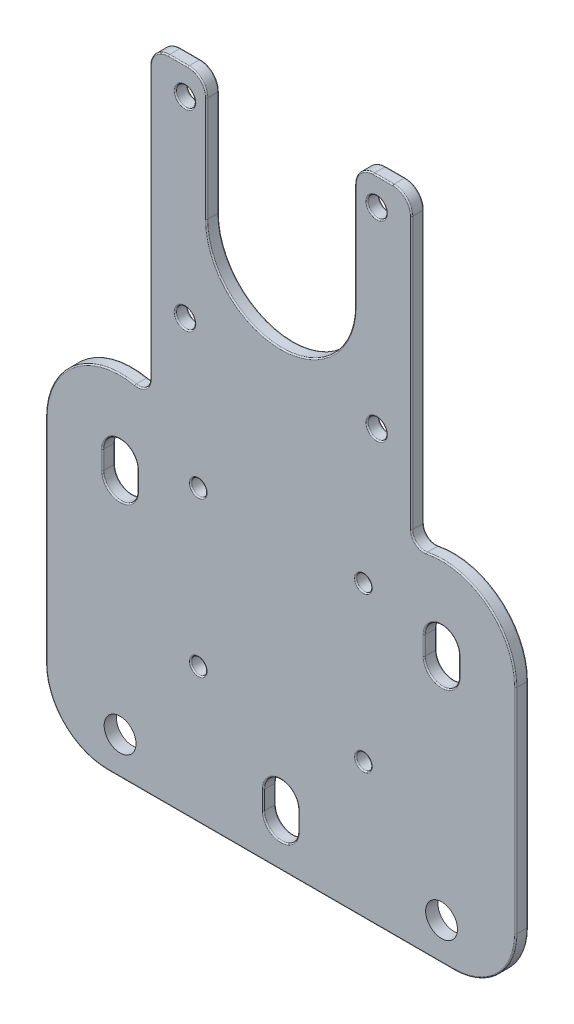
SolidWorks part; units mm, degrees
ref_plane "前视基准面" through (0, 0, 0) normal (0, 0, 1) x (1, 0, 0)
ref_plane "上视基准面" through (0, 0, 0) normal (0, 1, 0) x (1, 0, 0)
ref_plane "右视基准面" through (0, 0, 0) normal (1, 0, 0) x (0, 0, -1)
sketch "草图1" plane through (0, 0, 0) normal (0, 0, 1) x (1, 0, 0)
  line L0 (-21.15, 56.6196) -> (-21.15, 12.7264)
  line L1 (-26, -0.9804) -> (-26, -3.9804) construction
  line L2 (-15, 59.6196) -> (-18.15, 59.6196)
  line L3 (18.15, 59.6196) -> (15, 59.6196)
  line L4 (38, -0.9804) -> (38, -45.4804)
  line L5 (21.15, 56.6196) -> (21.15, 12.7264)
  line L6 (-26, -2.4804) -> (1.7366, -2.4804) construction
  line L7 (-12, 39.6196) -> (-12, 56.6196)
  line L8 (12, 39.6196) -> (12, 56.6196)
  line L9 (-28.8, -0.9804) -> (-28.8, -3.9804)
  line L10 (-23.2, -0.9804) -> (-23.2, -3.9804)
  line L11 (-28.8, -0.9804) -> (-28.8, -3.9804)
  line L12 (-23.2, -0.9804) -> (-23.2, -3.9804)
  line L13 (0, -2.4804) -> (0, -36.8304) construction
  line L14 (-38, -3.9804) -> (-26, -3.9804) construction
  line L15 (0, 39.6196) -> (0, -65.8157) construction
  line L16 (38, -45.4804) -> (-38, -45.4804)
  line L17 (-38, -0.9804) -> (-38, -45.4804)
  line L18 (-28.8, -0.9804) -> (-28.8, -3.9804)
  line L19 (-23.2, -0.9804) -> (-23.2, -3.9804)
  line L20 (-28.8, -0.9804) -> (-28.8, -3.9804)
  line L21 (-23.2, -0.9804) -> (-23.2, -3.9804)
  line L22 (-28.8, -0.9804) -> (-28.8, -3.9804)
  line L23 (-23.2, -0.9804) -> (-23.2, -3.9804)
  line L24 (-28.8, -0.9804) -> (-28.8, -3.9804)
  line L25 (-23.2, -0.9804) -> (-23.2, -3.9804)
  line L26 (-28.8, -0.9804) -> (-28.8, -3.9804)
  line L27 (-23.2, -0.9804) -> (-23.2, -3.9804)
  line L28 (-28.8, -0.9804) -> (-28.8, -3.9804)
  line L29 (-23.2, -0.9804) -> (-23.2, -3.9804)
  line L30 (28.8, -0.9804) -> (28.8, -3.9804)
  line L31 (23.2, -0.9804) -> (23.2, -3.9804)
  line L32 (2.8, -35.6304) -> (2.8, -38.6304)
  line L33 (2.8, -35.3304) -> (2.8, -38.3304)
  line L34 (0, -35.3304) -> (0, -38.3304) construction
  line L35 (2.8, -35.3304) -> (2.8, -38.3304)
  line L36 (2.8, -35.3304) -> (2.8, -38.3304)
  line L37 (2.8, -35.3304) -> (2.8, -38.3304)
  line L38 (-2.8, -35.6304) -> (-2.8, -38.6304)
  line L39 (-2.8, -35.3304) -> (-2.8, -38.3304)
  line L40 (-2.8, -35.3304) -> (-2.8, -38.3304)
  line L41 (-2.8, -35.3304) -> (-2.8, -38.3304)
  line L42 (2.8, -35.3304) -> (2.8, -38.3304)
  line L43 (-2.8, -35.3304) -> (-2.8, -38.3304)
  line L44 (2.8, -35.3304) -> (2.8, -38.3304)
  line L45 (2.8, -35.3304) -> (2.8, -38.3304)
  line L46 (-2.8, -35.3304) -> (-2.8, -38.3304)
  line L47 (-2.8, -35.3304) -> (-2.8, -38.3304)
  line L48 (-2.8, -35.3304) -> (-2.8, -38.3304)
  line L49 (0, -2.4804) -> (0, -37.1304) construction
  circle A2 centre (-15.5, 55.1196) radius 1.55
  circle A3 centre (15.5, 24.1196) radius 1.55
  circle A4 centre (-15.5, 24.1196) radius 1.55
  circle A5 centre (15.5, 55.1196) radius 1.55
  arc A6 (15, 59.6196) -> (12, 56.6196) centre (15, 56.6196) ccw
  arc A7 (-23.5571, 10.7683) -> (-21.15, 12.7264) centre (-23.15, 12.7264) ccw
  arc A8 (-23.5571, 10.7683) -> (-38, -0.9804) centre (-26, -0.9804) ccw
  arc A9 (23.5571, 10.7683) -> (21.15, 12.7264) centre (23.15, 12.7264) cw
  arc A10 (-18.15, 59.6196) -> (-21.15, 56.6196) centre (-18.15, 56.6196) ccw
  arc A11 (-12, 39.6196) -> (12, 39.6196) centre (0, 39.6196) ccw
  arc A12 (21.15, 56.6196) -> (18.15, 59.6196) centre (18.15, 56.6196) ccw
  arc A13 (23.5571, 10.7683) -> (38, -0.9804) centre (26, -0.9804) cw
  arc A14 (23.2, -0.9804) -> (28.8, -0.9804) centre (26, -0.9804) cw
  arc A15 (28.8, -3.9804) -> (23.2, -3.9804) centre (26, -3.9804) cw
  arc A16 (-12, 56.6196) -> (-15, 59.6196) centre (-15, 56.6196) ccw
  arc A17 (-23.2, -0.9804) -> (-28.8, -0.9804) centre (-26, -0.9804) ccw
  arc A18 (-28.8, -3.9804) -> (-23.2, -3.9804) centre (-26, -3.9804) ccw
  arc A19 (-2.8, -38.6304) -> (2.8, -38.6304) centre (0, -38.6304) ccw
  arc A20 (2.8, -35.6304) -> (-2.8, -35.6304) centre (0, -35.6304) ccw
  dimension "D3" = 12
  dimension "D4" = 2.8
  dimension "D6" = 35.5
  dimension "D1" = 2
  dimension "D9" = 56.1
  dimension "D11" = 2.8
  dimension "D12" = 4.5
  dimension "D2" = 34.65
  dimension "D5" = 31
  dimension "D7" = 5.65
  dimension "D8" = 5.65
  dimension "D10" = 26
extrude "凸台-拉伸2" add sketch "草图1" along normal blind 2 contours L7 A16 L2 A10 L0 A7 A8 L17 L16 L4 A13 A9 L5 A12 L3 A6 L8 A11 A20 L32 A19 L38 A18 L9 A17 L10 L30 A15 L31 A14 A2 A3 A4 A5
sketch "草图2" plane through (0, 0, 2) normal (0, 0, 1) x (1, 0, 0)
  line L0 (0, 27.6196) -> (0, -50.162) construction
  arc A0 (-12, 39.6196) -> (12, 39.6196) centre (0, 39.6196) ccw construction
sketch "草图3" plane through (0, 0, 2) normal (0, 0, 1) x (1, 0, 0)
  line L0 (38, -45.4804) -> (-38, -45.4804) construction
  line L1 (0, -41.4304) -> (0, 15.6863) construction
  line L2 (38, -0.9804) -> (38, -45.4804) construction
  circle A0 centre (13.35, 1.3996) radius 1.25
  circle A1 centre (13.35, -23.6004) radius 1.25
  arc A3 (-2.8, -38.6304) -> (2.8, -38.6304) centre (0, -38.6304) ccw construction
  circle A5 centre (-13.35, -23.6004) radius 1.25
  circle A7 centre (-13.35, 1.3996) radius 1.25
  dimension "D1" = 24.65
  dimension "D2" = 21.88
  dimension "D3" = 25
  dimension "D4" = 24.65
extrude "切除-拉伸1" cut sketch "草图3" against normal through all
fillet "圆角1" radius 10 2 edges at (38, -45.4804, 1) (-38, -45.4804, 1)
fillet "圆角2" radius 0.2 80 edges at (-35.0711, -42.5515, 2) (-38, -18.2304, 2) (-33.5725, 8.3285, 2) (-21.8879, 11.1749, 2) (-21.15, 34.673, 2) (-20.2713, 58.7409, 2) (-16.575, 59.6196, 2) (-12.8787, 58.7409, 2) (-12, 48.1196, 2) (0, 27.6196, 2) (12, 48.1196, 2) (12.8787, 58.7409, 2) (16.575, 59.6196, 2) (20.2713, 58.7409, 2) (21.15, 34.673, 2) (21.8879, 11.1749, 2) (33.5725, 8.3285, 2) (38, -18.2304, 2) (35.0711, -42.5515, 2) (0, -45.4804, 2) (17.05, 55.1196, 2) (-13.95, 24.1196, 2) (17.05, 24.1196, 2) (-13.95, 55.1196, 2) (26, 1.8196, 2) (23.2, -2.4804, 2) (26, -6.7804, 2) (28.8, -2.4804, 2) (-23.2, -2.4804, 2) (-26, 1.8196, 2) (-28.8, -2.4804, 2) (-26, -6.7804, 2) (-2.8, -37.1304, 2) (0, -41.4304, 2) (2.8, -37.1304, 2) (0, -32.8304, 2) (14.6, 1.3996, 2) (14.6, -23.6004, 2) (-14.6, -23.6004, 2) (-14.6, 1.3996, 2) (33.5725, 8.3285, 0) (21.8879, 11.1749, 0) (21.15, 34.673, 0) (20.2713, 58.7409, 0) (16.575, 59.6196, 0) (12.8787, 58.7409, 0) (12, 48.1196, 0) (0, 27.6196, 0) (-12, 48.1196, 0) (-12.8787, 58.7409, 0) (-16.575, 59.6196, 0) (-20.2713, 58.7409, 0) (-21.15, 34.673, 0) (-21.8879, 11.1749, 0) (-33.5725, 8.3285, 0) (-38, -18.2304, 0) (-35.0711, -42.5515, 0) (0, -45.4804, 0) (35.0711, -42.5515, 0) (38, -18.2304, 0) (17.05, 55.1196, 0) (-13.95, 24.1196, 0) (17.05, 24.1196, 0) (-13.95, 55.1196, 0) (26, -6.7804, 0) (23.2, -2.4804, 0) (26, 1.8196, 0) (28.8, -2.4804, 0) (-28.8, -2.4804, 0) (-26, 1.8196, 0) (-23.2, -2.4804, 0) (-26, -6.7804, 0) (2.8, -37.1304, 0) (0, -41.4304, 0) (-2.8, -37.1304, 0) (0, -32.8304, 0) (14.6, 1.3996, 0) (14.6, -23.6004, 0) (-14.6, -23.6004, 0) (-14.6, 1.3996, 0)
sketch "草图4" plane through (0, 0, 2) normal (0, 0, 1) x (1, 0, 0)
  line L0 (0, -45.4804) -> (0, -75.3016) construction
  line L1 (28, -45.4804) -> (-28, -45.4804) construction
  circle A0 centre (26, -39.4804) radius 2.575
  circle A1 centre (-26, -39.4804) radius 2.575
  dimension "D1" = 5.15
  dimension "D3" = 6
extrude "切除-拉伸2" cut sketch "草图4" against normal blind 10
